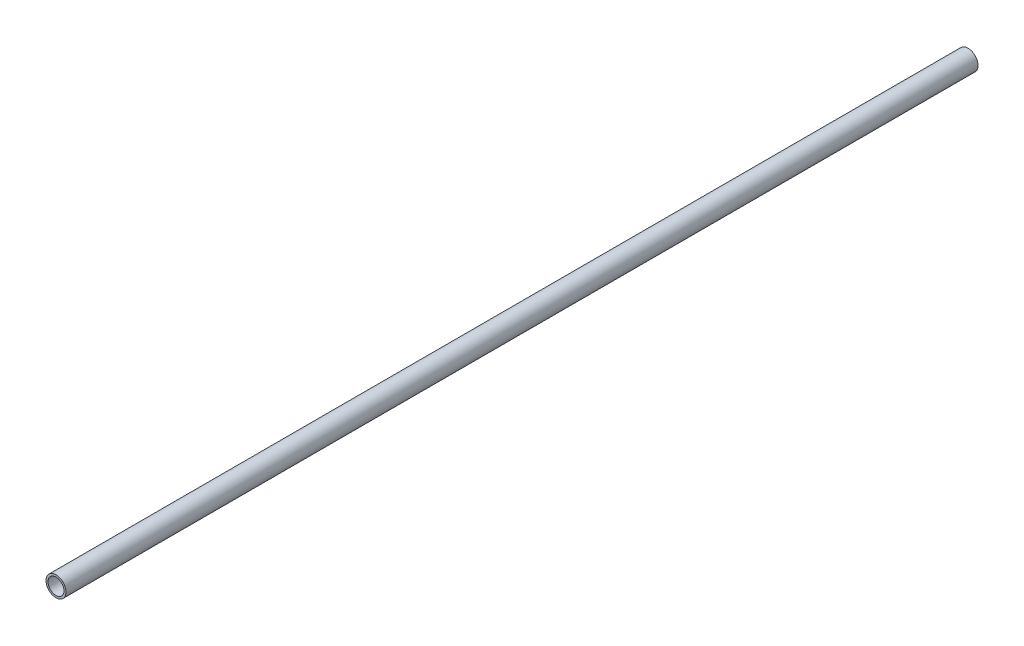
SolidWorks part; units mm, degrees
ref_plane "Front Plane" through (0, 0, 0) normal (0, 0, 1) x (1, 0, 0)
ref_plane "Top Plane" through (0, 0, 0) normal (0, 1, 0) x (1, 0, 0)
ref_plane "Right Plane" through (0, 0, 0) normal (1, 0, 0) x (0, 0, -1)
sketch "Sketch1" plane through (0, 0, 0) normal (0, 0, 1) x (1, 0, 0)
  circle A0 centre (-157.8902, 194.2706) radius 9.525
  circle A1 centre (-157.8902, 194.2706) radius 7.62
  dimension "D1" = 19.05
  dimension "D2" = 1.905
extrude "Boss-Extrude1" add sketch "Sketch1" along normal blind 869.696
